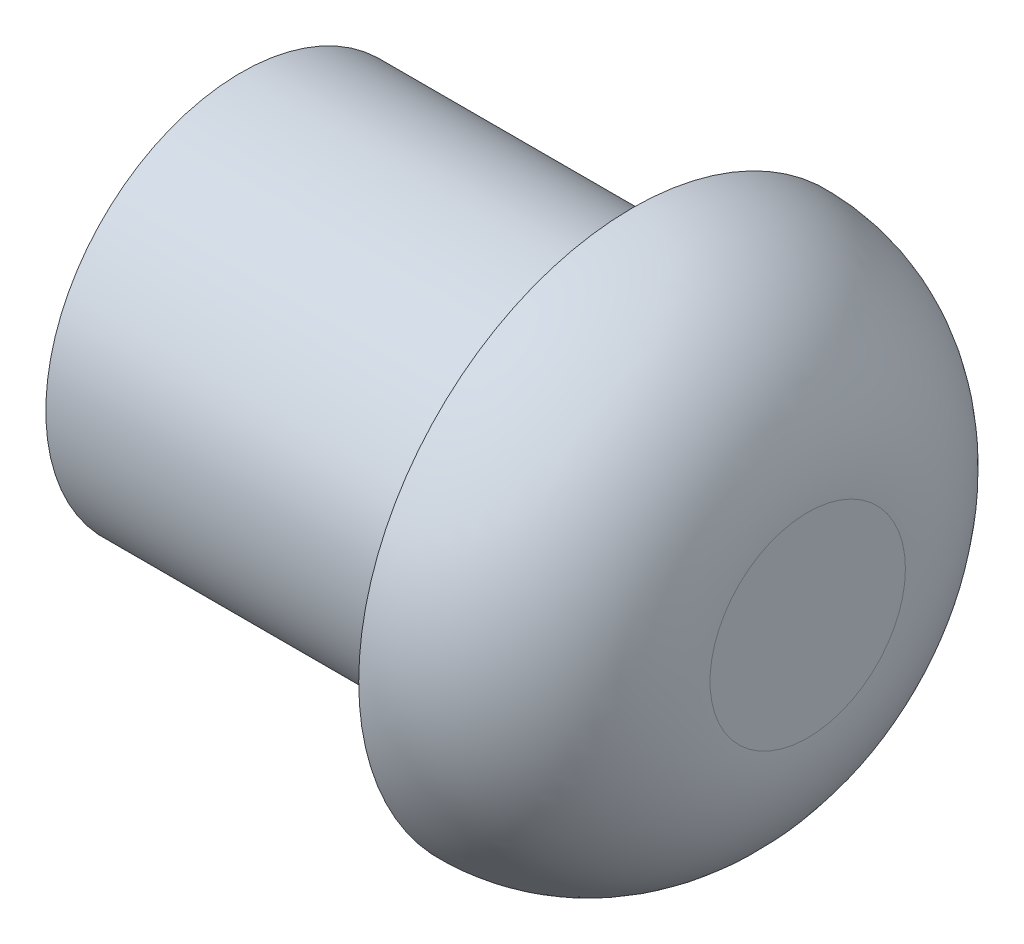
SolidWorks part; units mm, degrees
ref_plane "Front Plane" through (0, 0, 0) normal (0, 0, 1) x (1, 0, 0)
ref_plane "Top Plane" through (0, 0, 0) normal (0, 1, 0) x (1, 0, 0)
ref_plane "Right Plane" through (0, 0, 0) normal (1, 0, 0) x (0, 0, -1)
sketch "Sketch1" plane through (0, 0, 0) normal (0, 0, 1) x (1, 0, 0)
  line L0 (-24.8782, 0) -> (25.1218, 0)
  line L1 (25.1218, 0) -> (25.1218, -9.9711)
  line L3 (35.0929, 25) -> (-24.8782, 25)
  line L4 (-24.8782, 25) -> (-24.8782, 0)
  line L5 (47.5929, 12.5) -> (47.5929, 25)
  line L6 (47.5929, 25) -> (35.0929, 25)
  arc A1 (25.1218, -9.9711) -> (47.5929, 12.5) centre (25.1218, 12.5) ccw
  dimension "D1" = 50
  dimension "D2" = 25
revolve "Revolve1" add sketch "Sketch1" angle 360 about L6
